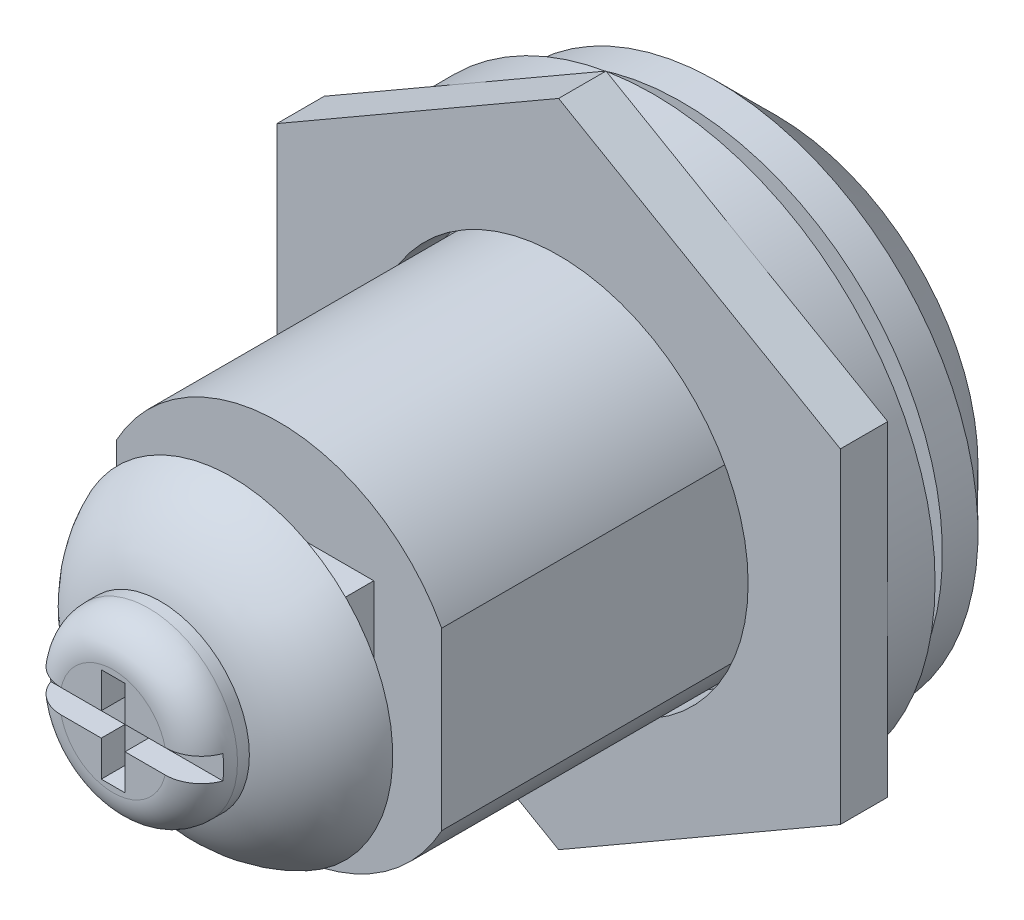
SolidWorks part; units mm, degrees
ref_plane "前视基准面" through (0, 0, 0) normal (0, 0, 1) x (1, 0, 0)
ref_plane "上视基准面" through (0, 0, 0) normal (0, 1, 0) x (1, 0, 0)
ref_plane "右视基准面" through (0, 0, 0) normal (1, 0, 0) x (0, 0, -1)
sketch "草图1" plane through (0, 0, 0) normal (0, 0, 1) x (1, 0, 0)
  line L0 (6.8666, 3.7) -> (6.8666, -3.7)
  line L1 (-6.8666, 3.7) -> (-6.8666, -3.7)
  line L2 (-15.0917, 0) -> (11.0145, 0) construction
  line L3 (0, 12.1407) -> (0, -11.873) construction
  arc A0 (-6.8666, -3.7) -> (6.8666, -3.7) centre (0, 0) ccw
  arc A1 (6.8666, 3.7) -> (-6.8666, 3.7) centre (0, 0) ccw
  dimension "D1" = 7.8
  dimension "D2" = 7.4
extrude "拉伸1" add sketch "草图1" along normal blind 17
sketch "草图3" plane through (0, 0, 0) normal (0, 0, -1) x (-1, 0, 0)
  circle A2 centre (0, 0) radius 11
  dimension "D1" = 22
extrude "拉伸2" add sketch "草图3" along normal blind 4
chamfer "倒角1" distance 2.5 angle 45 1 edges at (-11, 0, -4)
sketch "草图4" plane through (0, 0, 0) normal (0, 0, 1) x (1, 0, 0)
  line L4 (-7.1166, 3.7625) -> (-7.1166, -3.7625)
  line L5 (7.1166, -3.7625) -> (7.1166, 3.7625)
  arc A1 (-7.1166, -3.7625) -> (7.1166, -3.7625) centre (0, 0) ccw
  arc A2 (7.1166, 3.7625) -> (-7.1166, 3.7625) centre (0, 0) ccw
  circle A6 centre (0, 0) radius 11.5
  circle A7 centre (0, 0) radius 11.5
  dimension "D1" = 0.5
sketch "草图5" plane through (0, 0, 17) normal (0, 0, 1) x (1, 0, 0)
  line L0 (-14.5235, 0) -> (14.0386, 0) construction
  line L1 (0, 12.5838) -> (0, -12.2929) construction
  line L3 (-4, 4) -> (4, 4)
  line L4 (-4, 4) -> (-4, -4)
  line L5 (-4, -4) -> (4, -4)
  line L6 (4, 4) -> (4, -4)
  dimension "D1" = 8
  dimension "D2" = 8
extrude "拉伸4" add sketch "草图5" along normal blind 2
sketch "草图6" plane through (0, 0, 19) normal (0, 0, 1) x (1, 0, 0)
  line L0 (-9.4803, 0) -> (11.5, 0) construction
  line L1 (0, 7.3466) -> (0, -7.2011) construction
  circle A1 centre (0, 0) radius 2.5
  dimension "D1" = 5
extrude "拉伸5" add sketch "草图6" along normal blind 3
sketch "草图7" plane through (0, 0, 22) normal (0, 0, 1) x (1, 0, 0)
  circle A0 centre (0, 0) radius 3.75
  dimension "D1" = 7.5
extrude "拉伸6" add sketch "草图7" along normal blind 2
fillet "圆角1" radius 1.5 1 edges at (3.75, 0, 24)
sketch "草图8" plane through (0, 0, 24) normal (0, 0, 1) x (1, 0, 0)
  line L0 (-2.7105, 0) -> (2.6865, 0) construction
  line L1 (-4.5, 0.5) -> (-0.5, 0.5)
  line L2 (-4.5, 0.5) -> (-4.5, -0.5)
  line L3 (-4.5, -0.5) -> (-0.5, -0.5)
  line L4 (4.5, 0.5) -> (4.5, -0.5)
  line L5 (-0.5, 2) -> (0.5, 2)
  line L6 (-0.5, 2) -> (-0.5, 0.5)
  line L7 (-0.5, -2) -> (0.5, -2)
  line L8 (0.5, 2) -> (0.5, 0.5)
  line L9 (0, 3.1568) -> (0, -3.2539) construction
  line L10 (0.5, -0.5) -> (0.5, -2)
  line L11 (0.5, 0.5) -> (4.5, 0.5)
  line L12 (-0.5, -0.5) -> (-0.5, -2)
  line L13 (0.5, -0.5) -> (4.5, -0.5)
  dimension "D1" = 1
  dimension "D2" = 1
  dimension "D3" = 9
  dimension "D4" = 4
extrude "切除-拉伸1" cut sketch "草图8" against normal blind 1
ref_plane "基准面1" through (0, 0, 3.2) normal (0, 0, 1) x (1, 0, 0)
sketch "草图9" plane through (0, 0, 3.2) normal (0, 0, 1) x (1, 0, 0)
  line L0 (-23.5872, 0) -> (22.3691, 0) construction
  line L5 (0, 23.4548) -> (0, -20.323) construction
  line L8 (11.8901, -6.8648) -> (0, -13.7295)
  line L9 (-11.8901, -6.8648) -> (-11.8901, 6.8648)
  line L10 (0, 13.7295) -> (11.8901, 6.8648)
  line L11 (11.8901, 6.8648) -> (11.8901, -6.8648)
  line L12 (-11.8901, 6.8648) -> (0, 13.7295)
  line L13 (0, -13.7295) -> (-11.8901, -6.8648)
  arc A0 (6.8666, 3.7) -> (-6.8666, 3.7) centre (0, 0) ccw construction
  circle A3 centre (0, 0) radius 8
  dimension "D1" = 0.2
extrude "拉伸7" add sketch "草图9" along normal blind 2
sketch "草图10" plane through (0, 0, -4) normal (0, 0, -1) x (-1, 0, 0)
  line L1 (1, 3.5) -> (-1, 3.5)
  line L2 (1, 3.5) -> (1, -3.5)
  line L3 (1, -3.5) -> (-1, -3.5)
  line L4 (-1, 3.5) -> (-1, -3.5)
  line L5 (1, 3.5) -> (-1, -3.5) construction
  line L6 (1, -3.5) -> (-1, 3.5) construction
  point P0 (0, 0)
  dimension "D1" = 2
  dimension "D2" = 7
extrude "切除-拉伸2" cut sketch "草图10" against normal blind 3
sketch "草图12" plane through (0, 0, 0) normal (1, 0, 0) x (0, 0, -1)
  line L0 (0, 0) -> (-23.9772, 0) construction
  line L1 (-19, 0) -> (-19, -6.8)
  line L2 (-19, 0) -> (-22, 0) construction
  line L4 (-19, 4) -> (-19, -4) construction
  line L7 (-22, 0) -> (-19, 0)
  line L8 (-22, -2.5) -> (-22, 2.5) construction
  line L9 (-22, 0) -> (-22, -2.3)
  line L10 (-22, -3.75) -> (-22, 3.75) construction
  line L11 (-17, -7.8) -> (0, -7.8) construction
  arc A0 (-22, -2.3) -> (-19, -6.8) centre (-17.125, -2.3) ccw
  dimension "D1" = 2.3
  dimension "D2" = 1
revolve "旋转2" add sketch "草图12" angle 360 about L0
sketch "草图13" plane through (0, 0, 3.2) normal (0, 0, -1) x (-1, 0, 0)
  circle A0 centre (0, 0) radius 11.8901
extrude "凸台-拉伸2" add sketch "草图13" along normal blind 2
